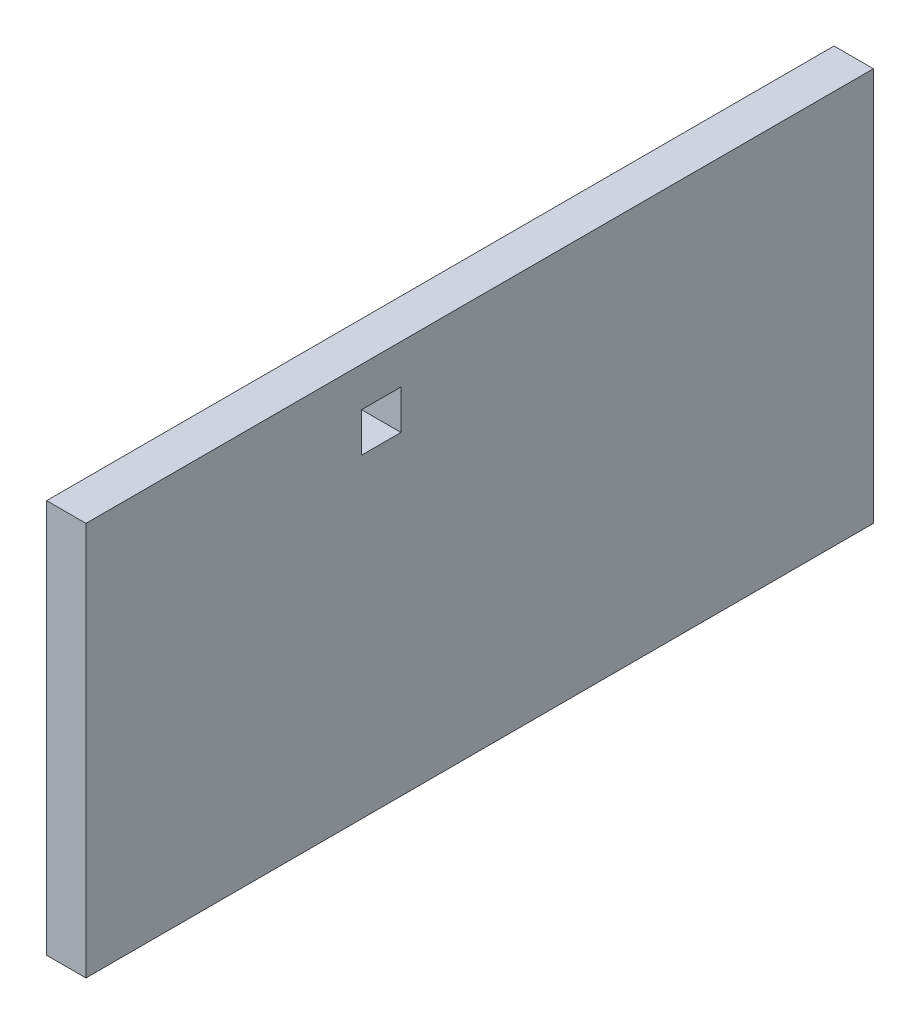
SolidWorks part; units mm, degrees
ref_plane "Front Plane" through (0, 0, 0) normal (1, 0, 0) x (0, 1, 0)
ref_plane "Top Plane" through (0, 0, 0) normal (0, 0, 1) x (0, 1, 0)
ref_plane "Right Plane" through (0, 0, 0) normal (0, 1, 0) x (-1, 0, 0)
sketch "Sketch1" plane through (0, 0, 0) normal (1, 0, 0) x (0, 1, 0)
  line L1 (-500, 0) -> (500, 0)
  line L2 (-500, 0) -> (-500, 1000)
  line L3 (-500, 1000) -> (500, 1000)
  line L4 (500, 0) -> (500, 1000)
  line L5 (-500, 0) -> (500, 1000) construction
  line L6 (-500, 1000) -> (500, 0) construction
  point P0 (0, 500)
  point P5 (0, 0)
  dimension "D1" = 1000
  dimension "D2" = 1000
extrude "Boss-Extrude1" add sketch "Sketch1" along normal mid plane 100
sketch "Sketch2" plane through (50, 0, 0) normal (1, 0, 0) x (0, 0, -1)
  line L0 (-500, -500) -> (-500, 500) construction
  line L1 (-1000, -500) -> (0, -500) construction
  line L2 (0, 500) -> (-1000, 500) construction
  line L3 (-500, 500) -> (0, 500) construction
  line L4 (-200, 300) -> (-300, 300)
  line L5 (-200, 300) -> (-200, 400)
  line L6 (-200, 400) -> (-300, 400)
  line L7 (-300, 300) -> (-300, 400)
  line L8 (-200, 300) -> (-300, 400) construction
  line L9 (-200, 400) -> (-300, 300) construction
  point P6 (-250, 350)
  point P11 (-250, 500)
  dimension "D1" = 100
  dimension "D2" = 100
  dimension "D3" = 100
extrude "Cut-Extrude1" cut sketch "Sketch2" against normal through all
sketch "Sketch3" plane through (0, 0, 0) normal (1, 0, 0) x (0, 1, 0)
  line L0 (-500, -1000) -> (500, -1000)
  line L1 (500, -1000) -> (500, 0)
  line L2 (500, 0) -> (-500, 0)
  line L3 (-500, 0) -> (-500, -1000)
extrude "Boss-Extrude2" add sketch "Sketch3" along normal mid plane 100
